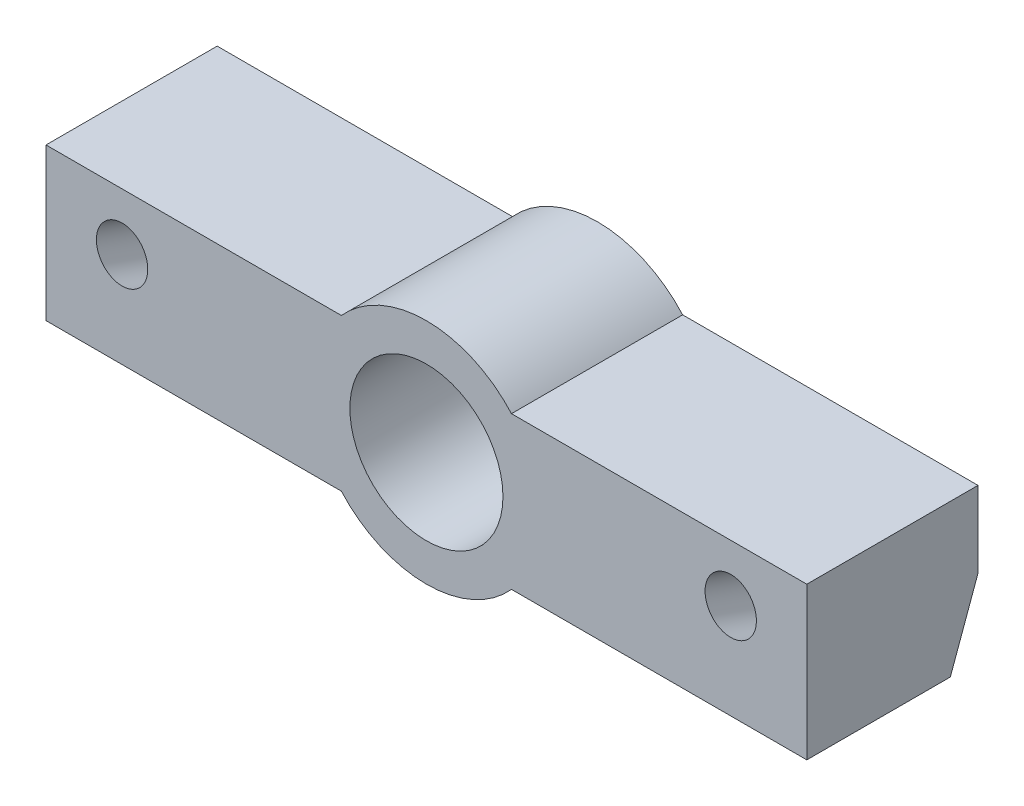
SolidWorks part; units mm, degrees
ref_plane "Front Plane" through (0, 0, 0) normal (0, 0, 1) x (1, 0, 0)
ref_plane "Top Plane" through (0, 0, 0) normal (0, 1, 0) x (1, 0, 0)
ref_plane "Right Plane" through (0, 0, 0) normal (1, 0, 0) x (0, 0, -1)
sketch "Sketch1" plane through (0, 0, 0) normal (0, 0, 1) x (1, 0, 0)
  line L6 (-4.4721, 4) -> (-20, 4)
  line L7 (20, 4) -> (4.4721, 4)
  line L8 (20, 4) -> (20, -4)
  line L9 (20, -4) -> (4.4721, -4)
  line L10 (-20, 4) -> (-20, -4)
  line L12 (-4.4721, -4) -> (-20, -4)
  line L13 (-20, 4) -> (0, 0) construction
  line L14 (0, 0) -> (20, 4) construction
  line L15 (-20, -4) -> (0, 0) construction
  arc A2 (4.4721, 4) -> (-4.4721, 4) centre (0, 0) ccw
  arc A3 (-4.4721, -4) -> (4.4721, -4) centre (0, 0) ccw
  dimension "D2" = 40
  dimension "D1" = 12
  dimension "D3" = 8
extrude "Boss-Extrude1" add sketch "Sketch1" along normal blind 9
sketch "Sketch11" plane through (0, 0, 9) normal (0, 0, 1) x (1, 0, 0)
  circle A0 centre (0, 0) radius 4.025
  dimension "D1" = 8.05
extrude "Cut-Extrude4" cut sketch "Sketch11" against normal blind 7
sketch "Sketch5" plane through (-20, 0, 0) normal (-1, 0, 0) x (0, 0, 1)
  line L0 (0, 0) -> (2.1838, -6)
  line L2 (2.1838, -6) -> (0, -6)
  line L3 (0, -6) -> (0, 0)
  line L4 (0, 4) -> (0, -4) construction
  line L5 (0, -6) -> (9, -6) construction
  point P3 (8.0686, -2.1155)
  point P4 (0, -0.6995)
  point P9 (3.388, -7.5454)
  point P10 (3.4262, -6)
  point P13 (0, 0)
  dimension "D1" = 20
extrude "Cut-Extrude2" cut sketch "Sketch5" against normal through all
sketch "Sketch12" plane through (0, 0, 0) normal (0, -0.342, -0.9397) x (-1, 0, 0)
  line L0 (-16, -2.1284) -> (16, -2.1284) construction
  line L1 (20, -4.2567) -> (20, 0) construction
  point P0 (-16, -2.1284)
  point P1 (16, -2.1284)
  point P3 (0, -2.1284)
  point P7 (20, -2.1284)
  dimension "D1" = 32
hole_wizard "Ø2.7 (2.7) Diameter Hole1" positions "Sketch12" profile "Sketch13" hole size "Ø2.7" standard "ANSI Metric" end condition through all
sketch "Sketch13" plane through (16, -2, 0.7279) normal (1, 0, 0) x (0, 0.9397, -0.342)
  line L0 (0, 0) -> (0, 10.5094)
  line L1 (0, 10.5094) -> (1.35, 10.5094)
  line L2 (1.35, 10.5094) -> (1.35, 0)
  line L5 (1.35, 0) -> (0, 0)
  line L11 (0, -6.35) -> (0, 107.95) construction
  dimension "Thru Hole Dia." = 2.7
  dimension "Thru Hole Depth" = 10.5094
